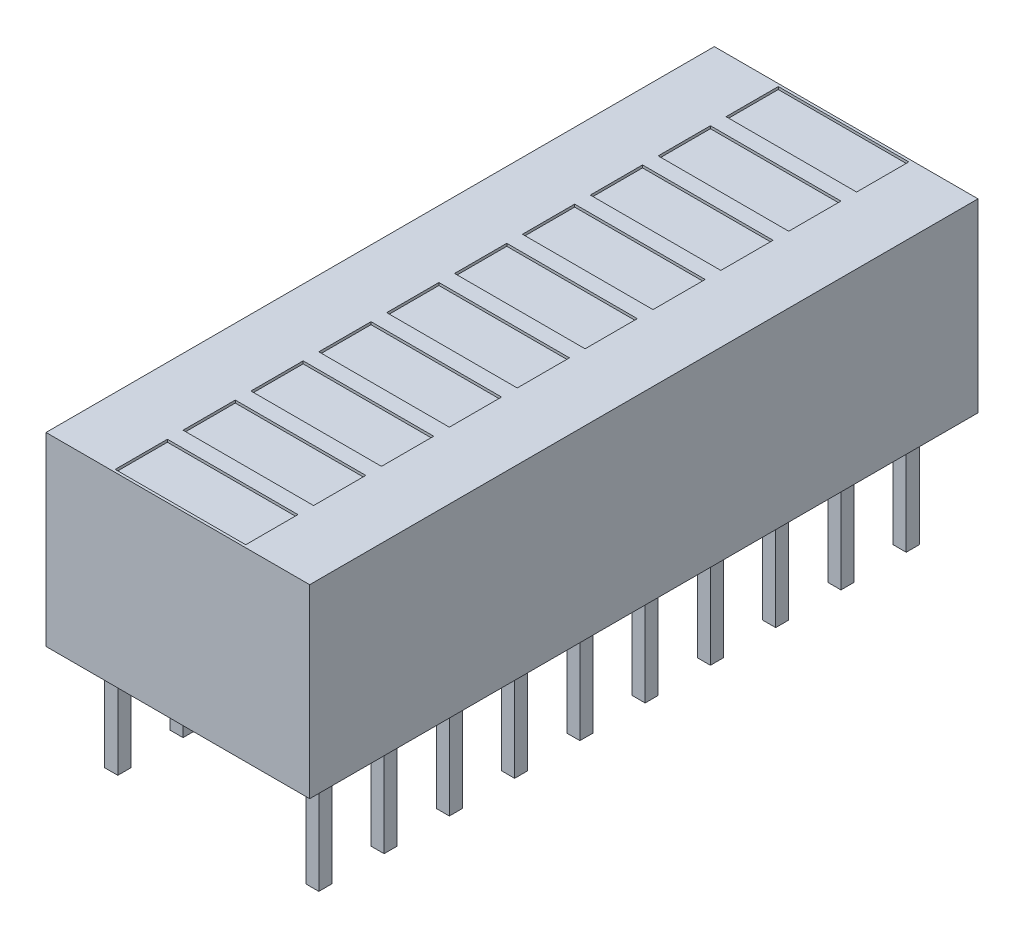
SolidWorks part; units mm, degrees
ref_plane "Front Plane" through (0, 0, 0) normal (0, 0, 1) x (1, 0, 0)
ref_plane "Top Plane" through (0, 0, 0) normal (0, 1, 0) x (1, 0, 0)
ref_plane "Right Plane" through (0, 0, 0) normal (1, 0, 0) x (0, 0, -1)
sketch "Sketch1" plane through (0, 0, 0) normal (0, 1, 0) x (1, 0, 0)
  line L1 (-5.05, -12.8) -> (5.05, -12.8)
  line L2 (-5.05, -12.8) -> (-5.05, 12.8)
  line L3 (-5.05, 12.8) -> (5.05, 12.8)
  line L4 (5.05, -12.8) -> (5.05, 12.8)
  line L5 (-5.05, -12.8) -> (5.05, 12.8) construction
  line L6 (-5.05, 12.8) -> (5.05, -12.8) construction
  point P0 (0, 0)
  dimension "D1" = 25.6
  dimension "10.1" = 10.1
extrude "Boss-Extrude1" add sketch "Sketch1" along normal blind 7.1
sketch "Sketch2" plane through (0, 0, 0) normal (0, 1, 0) x (1, 0, 0)
  line L0 (3.6, -11) -> (3.6, -11.5)
  line L1 (-4.1, -11) -> (-3.6, -11)
  line L2 (-4.1, -11) -> (-4.1, -11.5)
  line L3 (-4.1, -11.5) -> (-3.6, -11.5)
  line L4 (-3.6, -11) -> (-3.6, -11.5)
  line L5 (-4.1, -11) -> (-3.6, -11.5) construction
  line L6 (-4.1, -11.5) -> (-3.6, -11) construction
  line L7 (3.6, -11) -> (4.1, -11)
  line L8 (4.1, -11) -> (4.1, -11.5)
  line L9 (3.6, -11.5) -> (4.1, -11.5)
  line L10 (3.6, -8.5) -> (3.6, -9)
  line L11 (3.6, -8.5) -> (4.1, -8.5)
  line L12 (4.1, -8.5) -> (4.1, -9)
  line L13 (3.6, -9) -> (4.1, -9)
  line L14 (3.6, -6) -> (3.6, -6.5)
  line L15 (3.6, -6) -> (4.1, -6)
  line L16 (4.1, -6) -> (4.1, -6.5)
  line L17 (3.6, -6.5) -> (4.1, -6.5)
  line L18 (3.6, -3.5) -> (3.6, -4)
  line L19 (3.6, -3.5) -> (4.1, -3.5)
  line L20 (4.1, -3.5) -> (4.1, -4)
  line L21 (3.6, -4) -> (4.1, -4)
  line L22 (3.6, -1) -> (3.6, -1.5)
  line L23 (3.6, -1) -> (4.1, -1)
  line L24 (4.1, -1) -> (4.1, -1.5)
  line L25 (3.6, -1.5) -> (4.1, -1.5)
  line L26 (3.6, 1.5) -> (3.6, 1)
  line L27 (3.6, 1.5) -> (4.1, 1.5)
  line L28 (4.1, 1.5) -> (4.1, 1)
  line L29 (3.6, 1) -> (4.1, 1)
  line L30 (3.6, 4) -> (3.6, 3.5)
  line L31 (3.6, 4) -> (4.1, 4)
  line L32 (4.1, 4) -> (4.1, 3.5)
  line L33 (3.6, 3.5) -> (4.1, 3.5)
  line L34 (3.6, 6.5) -> (3.6, 6)
  line L35 (3.6, 6.5) -> (4.1, 6.5)
  line L36 (4.1, 6.5) -> (4.1, 6)
  line L37 (3.6, 6) -> (4.1, 6)
  line L38 (3.6, 9) -> (3.6, 8.5)
  line L39 (3.6, 9) -> (4.1, 9)
  line L40 (4.1, 9) -> (4.1, 8.5)
  line L41 (3.6, 8.5) -> (4.1, 8.5)
  line L42 (3.6, 11.5) -> (3.6, 11)
  line L43 (3.6, 11.5) -> (4.1, 11.5)
  line L44 (4.1, 11.5) -> (4.1, 11)
  line L45 (3.6, 11) -> (4.1, 11)
  line L46 (-4.1, -8.5) -> (-4.1, -9)
  line L47 (-4.1, -8.5) -> (-3.6, -8.5)
  line L48 (-3.6, -8.5) -> (-3.6, -9)
  line L49 (-4.1, -9) -> (-3.6, -9)
  line L50 (-4.1, -6) -> (-4.1, -6.5)
  line L51 (-4.1, -6) -> (-3.6, -6)
  line L52 (-3.6, -6) -> (-3.6, -6.5)
  line L53 (-4.1, -6.5) -> (-3.6, -6.5)
  line L54 (-4.1, -3.5) -> (-4.1, -4)
  line L55 (-4.1, -3.5) -> (-3.6, -3.5)
  line L56 (-3.6, -3.5) -> (-3.6, -4)
  line L57 (-4.1, -4) -> (-3.6, -4)
  line L58 (-4.1, -1) -> (-4.1, -1.5)
  line L59 (-4.1, -1) -> (-3.6, -1)
  line L60 (-3.6, -1) -> (-3.6, -1.5)
  line L61 (-4.1, -1.5) -> (-3.6, -1.5)
  line L62 (-4.1, 1.5) -> (-4.1, 1)
  line L63 (-4.1, 1.5) -> (-3.6, 1.5)
  line L64 (-3.6, 1.5) -> (-3.6, 1)
  line L65 (-4.1, 1) -> (-3.6, 1)
  line L66 (-4.1, 4) -> (-4.1, 3.5)
  line L67 (-4.1, 4) -> (-3.6, 4)
  line L68 (-3.6, 4) -> (-3.6, 3.5)
  line L69 (-4.1, 3.5) -> (-3.6, 3.5)
  line L70 (-4.1, 6.5) -> (-4.1, 6)
  line L71 (-4.1, 6.5) -> (-3.6, 6.5)
  line L72 (-3.6, 6.5) -> (-3.6, 6)
  line L73 (-4.1, 6) -> (-3.6, 6)
  line L74 (-4.1, 9) -> (-4.1, 8.5)
  line L75 (-4.1, 9) -> (-3.6, 9)
  line L76 (-3.6, 9) -> (-3.6, 8.5)
  line L77 (-4.1, 8.5) -> (-3.6, 8.5)
  line L78 (-4.1, 11.5) -> (-4.1, 11)
  line L79 (-4.1, 11.5) -> (-3.6, 11.5)
  line L80 (-3.6, 11.5) -> (-3.6, 11)
  line L81 (-4.1, 11) -> (-3.6, 11)
  point P0 (-3.85, -11.25)
  point P5 (-4.1, -11.25)
  point P7 (0, 0)
  dimension "D1" = 0.5
  dimension "D2" = 4.1
  dimension "D3" = 11.5
  dimension "D6" = 4.1
  dimension "D7" = 11.5
  dimension "D4" = 2
  dimension "D5" = 10
extrude "Boss-Extrude2" add sketch "Sketch2" against normal blind 4.2
sketch "Sketch3" plane through (0, 7.1, 0) normal (0, 1, 0) x (1, 0, 0)
  line L0 (-2.5, 8.1) -> (-2.5, 10.1)
  line L1 (-2.5, 10.7) -> (2.5, 10.7)
  line L2 (-2.5, 10.7) -> (-2.5, 12.7)
  line L3 (-2.5, 12.7) -> (2.5, 12.7)
  line L4 (2.5, 10.7) -> (2.5, 12.7)
  line L5 (-2.5, 10.7) -> (2.5, 12.7) construction
  line L6 (-2.5, 12.7) -> (2.5, 10.7) construction
  line L7 (-2.5, 8.1) -> (2.5, 8.1)
  line L8 (2.5, 8.1) -> (2.5, 10.1)
  line L9 (-2.5, 10.1) -> (2.5, 10.1)
  line L10 (-2.5, 5.5) -> (-2.5, 7.5)
  line L11 (-2.5, 5.5) -> (2.5, 5.5)
  line L12 (2.5, 5.5) -> (2.5, 7.5)
  line L13 (-2.5, 7.5) -> (2.5, 7.5)
  line L14 (-2.5, 2.9) -> (-2.5, 4.9)
  line L15 (-2.5, 2.9) -> (2.5, 2.9)
  line L16 (2.5, 2.9) -> (2.5, 4.9)
  line L17 (-2.5, 4.9) -> (2.5, 4.9)
  line L18 (-2.5, 0.3) -> (-2.5, 2.3)
  line L19 (-2.5, 0.3) -> (2.5, 0.3)
  line L20 (2.5, 0.3) -> (2.5, 2.3)
  line L21 (-2.5, 2.3) -> (2.5, 2.3)
  line L22 (-2.5, -2.3) -> (-2.5, -0.3)
  line L23 (-2.5, -2.3) -> (2.5, -2.3)
  line L24 (2.5, -2.3) -> (2.5, -0.3)
  line L25 (-2.5, -0.3) -> (2.5, -0.3)
  line L26 (-2.5, -4.9) -> (-2.5, -2.9)
  line L27 (-2.5, -4.9) -> (2.5, -4.9)
  line L28 (2.5, -4.9) -> (2.5, -2.9)
  line L29 (-2.5, -2.9) -> (2.5, -2.9)
  line L30 (-2.5, -7.5) -> (-2.5, -5.5)
  line L31 (-2.5, -7.5) -> (2.5, -7.5)
  line L32 (2.5, -7.5) -> (2.5, -5.5)
  line L33 (-2.5, -5.5) -> (2.5, -5.5)
  line L34 (-2.5, -10.1) -> (-2.5, -8.1)
  line L35 (-2.5, -10.1) -> (2.5, -10.1)
  line L36 (2.5, -10.1) -> (2.5, -8.1)
  line L37 (-2.5, -8.1) -> (2.5, -8.1)
  line L38 (-2.5, -12.7) -> (-2.5, -10.7)
  line L39 (-2.5, -12.7) -> (2.5, -12.7)
  line L40 (2.5, -12.7) -> (2.5, -10.7)
  line L41 (-2.5, -10.7) -> (2.5, -10.7)
  line L42 (0, 0.3) -> (0, -0.3) construction
  point P0 (0, 11.7)
  point P44 (0, 0)
  dimension "D1" = 5
  dimension "D2" = 2
  dimension "D4" = 0.6
  dimension "D3" = 10
extrude "Cut-Extrude1" cut sketch "Sketch3" against normal blind 0.1
equation "\"D6@Sketch2\"=\"D2@Sketch2\""
equation "\"D7@Sketch2\"=\"D3@Sketch2\""
